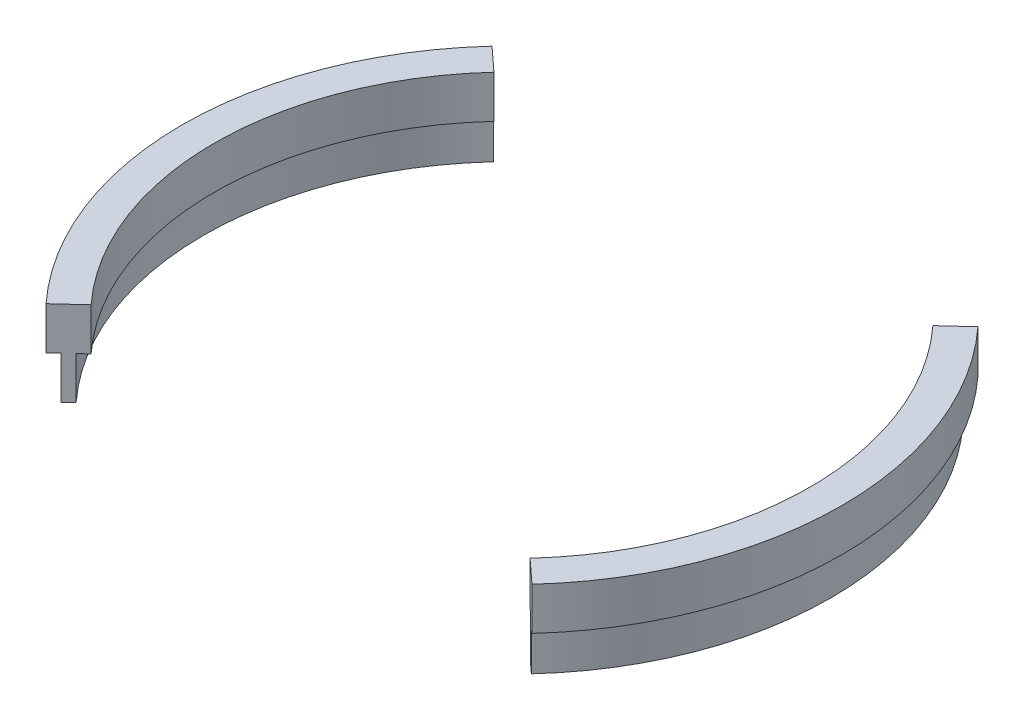
SolidWorks part; units mm, degrees
ref_plane "Front Plane" through (0, 0, 0) normal (0, 0, 1) x (1, 0, 0)
ref_plane "Top Plane" through (0, 0, 0) normal (0, 1, 0) x (1, 0, 0)
ref_plane "Right Plane" through (0, 0, 0) normal (1, 0, 0) x (0, 0, -1)
sketch "Sketch1" plane through (0, 0, 0) normal (0, 1, 0) x (1, 0, 0)
  line L0 (1.395, 33.1732) -> (1.395, -66.8268) construction
  line L1 (-20.7074, 3.4583) -> (-19.9707, 2.7821)
  line L2 (-20.7074, -37.1119) -> (-19.9707, -36.4357)
  line L3 (22.7606, -36.4357) -> (23.4974, -37.1119)
  line L4 (22.7606, 2.7821) -> (23.4974, 3.4583)
  arc A0 (-20.7074, 3.4583) -> (-20.7074, -37.1119) centre (1.395, -16.8268) ccw
  arc A1 (-19.9707, 2.7821) -> (-19.9707, -36.4357) centre (1.395, -16.8268) ccw
  arc A2 (22.7606, -36.4357) -> (22.7606, 2.7821) centre (1.395, -16.8268) ccw
  arc A3 (23.4974, -37.1119) -> (23.4974, 3.4583) centre (1.395, -16.8268) ccw
  dimension "D2" = 60
extrude "Boss-Extrude1" add sketch "Sketch1" along normal blind 4
sketch "Sketch2" plane through (0, 4, 0) normal (0, 1, 0) x (1, 0, 0)
  line L0 (-20.4366, 3.2097) -> (-36857.7489, 33811.6764) construction
  line L2 (-20.7074, -37.1119) -> (36816.6049, 33771.3548) construction
  line L4 (-21.4442, 4.1345) -> (-19.2339, 2.106)
  line L5 (-19.2339, -35.7595) -> (-21.4442, -37.788)
  line L6 (22.0239, -35.7595) -> (24.2341, -37.788)
  line L7 (24.2341, 4.1345) -> (22.0239, 2.106)
  arc A0 (-21.4442, 4.1345) -> (-21.4442, -37.788) centre (1.395, -16.8268) ccw
  arc A1 (-19.2339, 2.106) -> (-19.2339, -35.7595) centre (1.395, -16.8268) ccw
  arc A2 (-20.7074, 3.4583) -> (-20.7074, -37.1119) centre (1.395, -16.8268) ccw construction
  arc A3 (-19.9707, 2.7821) -> (-19.9707, -36.4357) centre (1.395, -16.8268) ccw construction
  arc A4 (24.2341, -37.788) -> (24.2341, 4.1345) centre (1.395, -16.8268) ccw
  arc A5 (22.0239, -35.7595) -> (22.0239, 2.106) centre (1.395, -16.8268) ccw
  dimension "D1" = 1
  dimension "D2" = 1
extrude "Boss-Extrude2" add sketch "Sketch2" along normal blind 4
